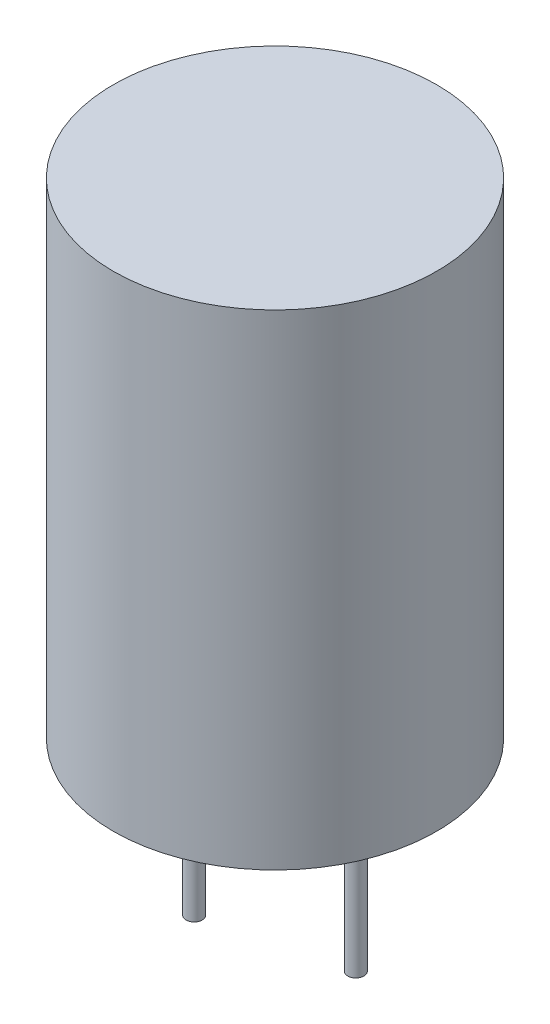
SolidWorks part; units mm, degrees
ref_plane "前视基准面" through (0, 0, 0) normal (0, 0, 1) x (1, 0, 0)
ref_plane "上视基准面" through (0, 0, 0) normal (0, 1, 0) x (1, 0, 0)
ref_plane "右视基准面" through (0, 0, 0) normal (1, 0, 0) x (0, 0, -1)
sketch "草图1" plane through (0, 0, 0) normal (0, 1, 0) x (1, 0, 0)
  circle A0 centre (0, 0) radius 10
  dimension "D1" = 20
extrude "拉伸1" add sketch "草图1" along normal blind 30
sketch "草图2" plane through (0, 0, 0) normal (0, -1, 0) x (1, 0, 0)
  line L0 (4.8023, 0) -> (-11.2367, 0) construction
  circle A0 centre (-5, 0) radius 0.5
  dimension "D2" = 1
  dimension "D1" = 5
extrude "拉伸2" add sketch "草图2" along normal blind 12
sketch "草图3" plane through (0, 0, 0) normal (0, -1, 0) x (1, 0, 0)
  line L0 (7.1249, 0) -> (-2.8562, 0) construction
  circle A0 centre (5, 0) radius 0.5
  dimension "D1" = 1
  dimension "D2" = 5
extrude "拉伸3" add sketch "草图3" along normal blind 10
